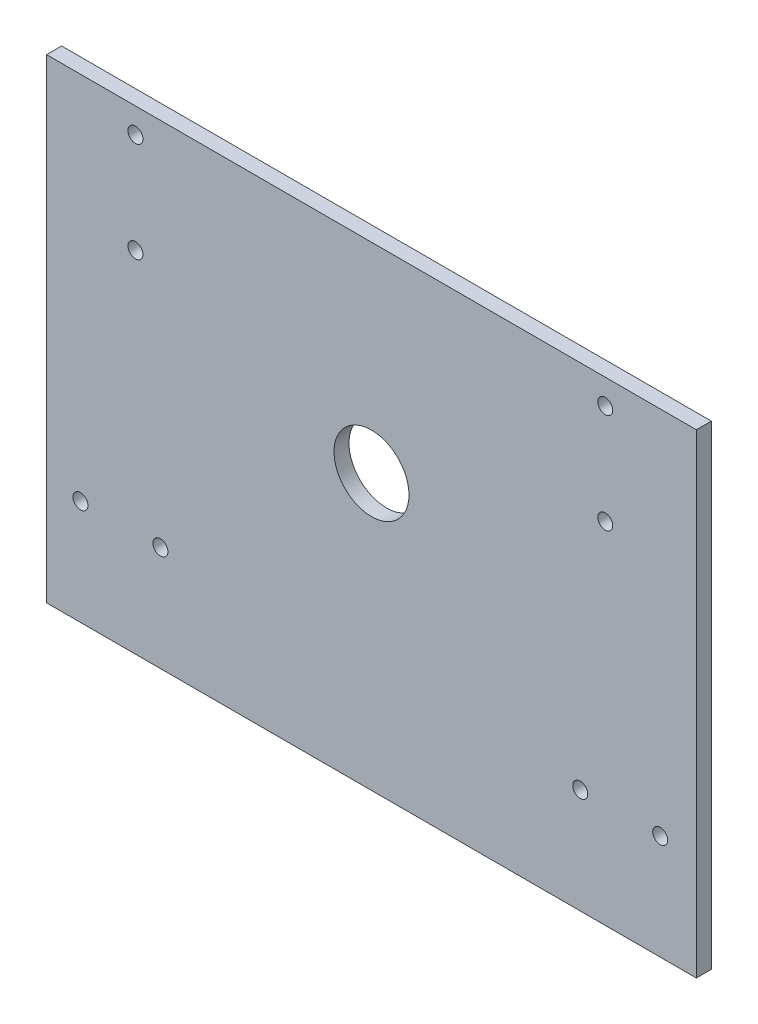
SolidWorks part; units mm, degrees
ref_plane "前视基准面" through (0, 0, 0) normal (0, 0, 1) x (1, 0, 0)
ref_plane "上视基准面" through (0, 0, 0) normal (0, 1, 0) x (1, 0, 0)
ref_plane "右视基准面" through (0, 0, 0) normal (1, 0, 0) x (0, 0, -1)
sketch "草图1" plane through (0, 0, 0) normal (0, 0, 1) x (1, 0, 0)
  line L1 (65, -47.5) -> (-65, -47.5)
  line L2 (65, -47.5) -> (65, 47.5)
  line L3 (65, 47.5) -> (-65, 47.5)
  line L4 (-65, -47.5) -> (-65, 47.5)
  line L5 (65, -47.5) -> (-65, 47.5) construction
  line L6 (65, 47.5) -> (-65, -47.5) construction
  point P0 (0, 0)
  dimension "D1" = 130
  dimension "D2" = 95
extrude "凸台-拉伸1" add sketch "草图1" along normal blind 3
sketch "草图2" plane through (0, 0, 3) normal (0, 0, 1) x (1, 0, 0)
  line L0 (0, -47.5) -> (0, -26.5) construction
  line L1 (-65, -47.5) -> (65, -47.5) construction
  line L2 (0, -26.5) -> (10, -26.5) construction
  circle A0 centre (10, -26.5) radius 1.5
  circle A1 centre (-10, -26.5) radius 1.5
  dimension "D3" = 3
  dimension "D1" = 21
  dimension "D2" = 10
sketch "草图3" plane through (0, 0, 0) normal (0, 0, -1) x (-1, 0, 0)
  circle A0 centre (-57.7671, -26.5) radius 1.5
  circle A1 centre (-41.7671, -26.5) radius 1.5
  circle A2 centre (42.2329, -26.5) radius 1.5
  circle A4 centre (58.2329, -26.5) radius 1.5
extrude "切除-拉伸2" cut sketch "草图3" against normal blind 10
sketch "草图4" plane through (0, 0, 0) normal (0, 0, -1) x (-1, 0, 0)
  circle A0 centre (-46.7671, 42.5) radius 1.5
  circle A1 centre (-46.7671, 22.5) radius 1.5
  circle A2 centre (47.2329, 42.5) radius 1.5
  circle A3 centre (47.2329, 22.5) radius 1.5
extrude "切除-拉伸3" cut sketch "草图4" against normal blind 10
sketch "草图5" plane through (0, 0, 3) normal (0, 0, 1) x (1, 0, 0)
  circle A0 centre (0, 7.4526) radius 7.5
  dimension "D1" = 15
extrude "切除-拉伸4" cut sketch "草图5" against normal blind 10
